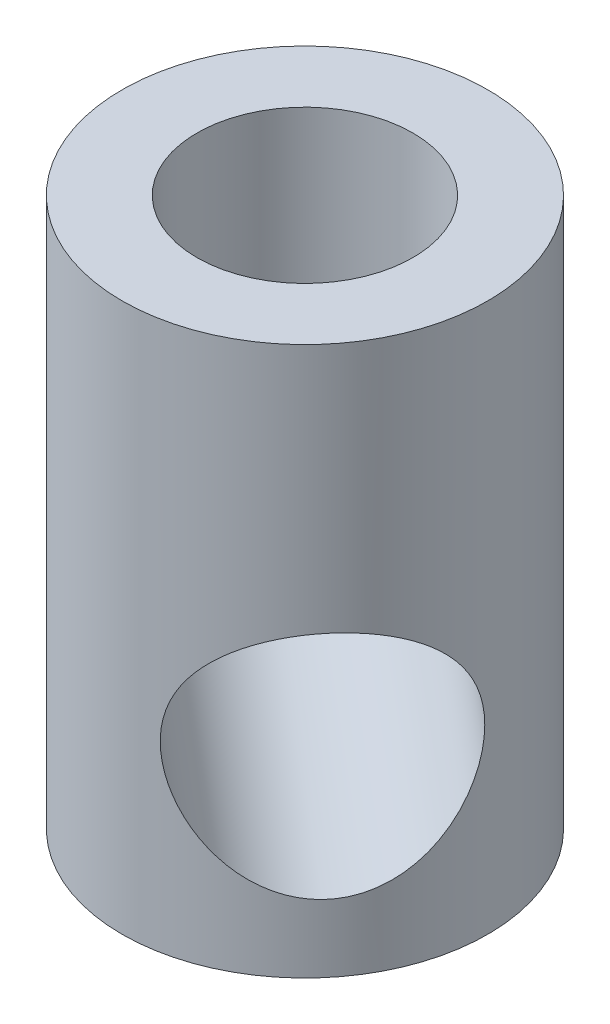
SolidWorks part; units mm, degrees
ref_plane "Front Plane" through (0, 0, 0) normal (0, 0, 1) x (1, 0, 0)
ref_plane "Top Plane" through (0, 0, 0) normal (0, 1, 0) x (1, 0, 0)
ref_plane "Right Plane" through (0, 0, 0) normal (1, 0, 0) x (0, 0, -1)
sketch "Sketch1" plane through (0, 0, 0) normal (0, 1, 0) x (1, 0, 0)
  circle A0 centre (0, 0) radius 25.4
extrude "Boss-Extrude1" add sketch "Sketch1" along normal blind 76.2
sketch "Sketch2" plane through (0, 76.2, 0) normal (0, 1, 0) x (1, 0, 0)
  circle A0 centre (0, 0) radius 15
extrude "Cut-Extrude1" cut sketch "Sketch2" against normal blind 25.4
hole_wizard "Ø12.8 (12.8) Diameter Hole1" positions "3DSketch1" profile "Sketch3" hole size "Ø12.8" standard "Ansi Metric" end condition through all
sketch3d "3DSketch1"
  line L0 (0, 0, 0) -> (19.4617, 0, 16.3219)
  line L1 (19.4617, 0, 16.3219) -> (19.4617, 25.4, 16.3219)
  circle A0 centre (0, 0, 0) radius 25.4 construction
  point P0 (19.4617, 25.4, 16.3219)
  point P7 (0, 25.4, 0)
  dimension "D1" = 25.4
sketch "Sketch3" plane through (19.4617, 25.4, 16.3219) normal (0, 1, 0) x (0.6426, 0, -0.7662)
  line L0 (0, 0) -> (0, 61.1835)
  line L1 (0, 61.1835) -> (16, 61.1835)
  line L2 (16, 61.1835) -> (16, 0)
  line L5 (16, 0) -> (0, 0)
  line L11 (0, -6.35) -> (0, 107.95) construction
  dimension "Thru Hole Dia." = 32
  dimension "Thru Hole Depth" = 61.1835
